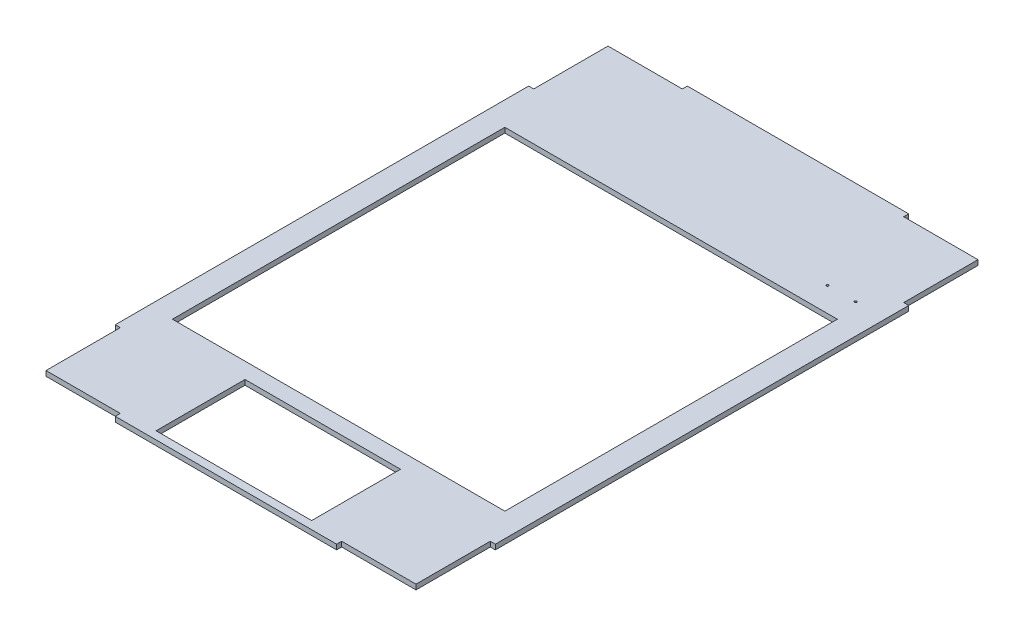
SolidWorks part; units mm, degrees
ref_plane "Front Plane" through (0, 0, 0) normal (0, 0, 1) x (1, 0, 0)
ref_plane "Top Plane" through (0, 0, 0) normal (0, 1, 0) x (1, 0, 0)
ref_plane "Right Plane" through (0, 0, 0) normal (1, 0, 0) x (0, 0, -1)
sketch "Sketch1" plane through (0, 0, 0) normal (0, 1, 0) x (1, 0, 0)
  line L1 (-209.5, -209.5) -> (209.5, -209.5)
  line L2 (-209.5, -209.5) -> (-209.5, 209.5)
  line L3 (-209.5, 209.5) -> (209.5, 209.5)
  line L4 (209.5, -209.5) -> (209.5, 209.5)
  line L5 (-209.5, -209.5) -> (209.5, 209.5) construction
  line L6 (-209.5, 209.5) -> (209.5, -209.5) construction
  line L7 (-239.5, -351.5) -> (239.5, -351.5)
  line L8 (-239.5, -351.5) -> (-239.5, 369.5)
  line L9 (-239.5, 369.5) -> (239.5, 369.5)
  line L10 (239.5, -351.5) -> (239.5, 369.5)
  line L11 (-98, -341.5) -> (98, -341.5)
  line L12 (-98, -341.5) -> (-98, -229.5)
  line L13 (-98, -229.5) -> (98, -229.5)
  line L14 (98, -341.5) -> (98, -229.5)
  line L15 (-98, -341.5) -> (98, -229.5) construction
  line L16 (-98, -229.5) -> (98, -341.5) construction
  point P0 (0, 0)
  point P6 (0, 0)
  point P11 (0, -351.5)
  point P12 (0, -285.5)
  dimension "D1" = 419
  dimension "D2" = 30
  dimension "D3" = 10
  dimension "D4" = 160
  dimension "D5" = 196
  dimension "D6" = 112
  dimension "D7" = 20
extrude "Boss-Extrude1" add sketch "Sketch1" along normal mid plane 6.35
sketch "Sketch2" plane through (0, 3.175, 0) normal (0, 1, 0) x (1, 0, 0)
  line L0 (-239.5, 369.5) -> (-239.5, 269.5)
  line L1 (-239.5, 369.5) -> (-239.5, -351.5) construction
  line L2 (-239.5, 269.5) -> (-233.15, 269.5)
  line L3 (-233.15, 269.5) -> (-233.15, 363.15)
  line L4 (-233.15, 363.15) -> (-139.5, 363.15)
  line L5 (-139.5, 363.15) -> (-139.5, 369.5)
  line L6 (239.5, 369.5) -> (-239.5, 369.5) construction
  line L7 (-139.5, 369.5) -> (-239.5, 369.5)
  line L8 (239.5, 369.5) -> (139.5, 369.5)
  line L9 (139.5, 369.5) -> (139.5, 363.15)
  line L10 (139.5, 363.15) -> (233.15, 363.15)
  line L11 (233.15, 363.15) -> (233.15, 269.5)
  line L12 (233.15, 269.5) -> (239.5, 269.5)
  line L13 (239.5, -351.5) -> (239.5, 369.5) construction
  line L14 (239.5, 269.5) -> (239.5, 369.5)
  line L15 (239.5, -351.5) -> (239.5, -251.5)
  line L16 (239.5, -251.5) -> (233.15, -251.5)
  line L17 (233.15, -251.5) -> (233.15, -345.15)
  line L18 (233.15, -345.15) -> (139.5, -345.15)
  line L19 (139.5, -345.15) -> (139.5, -351.5)
  line L20 (-239.5, -351.5) -> (239.5, -351.5) construction
  line L21 (139.5, -351.5) -> (239.5, -351.5)
  line L22 (-239.5, -351.5) -> (-139.5, -351.5)
  line L23 (-139.5, -351.5) -> (-139.5, -345.15)
  line L24 (-139.5, -345.15) -> (-233.15, -345.15)
  line L25 (-233.15, -345.15) -> (-233.15, -251.5)
  line L26 (-233.15, -251.5) -> (-239.5, -251.5)
  line L27 (-239.5, -251.5) -> (-239.5, -351.5)
  dimension "D1" = 100
  dimension "D2" = 6.35
extrude "Cut-Extrude1" cut sketch "Sketch2" against normal through all
sketch "Sketch3" plane through (0, 3.175, 0) normal (0, 1, 0) x (1, 0, 0)
  line L0 (201.88, 240.12) -> (166.32, 240.12) construction
  line L2 (209.5, 209.5) -> (-209.5, 209.5) construction
  line L3 (161.24, 232.5) -> (209.5, 232.5) construction
  line L4 (161.24, 232.5) -> (161.24, 268.06) construction
  line L5 (161.24, 268.06) -> (209.5, 268.06) construction
  line L6 (209.5, 232.5) -> (209.5, 268.06) construction
  line L7 (209.5, -209.5) -> (209.5, 209.5) construction
  circle A0 centre (166.32, 240.12) radius 1.375
  circle A1 centre (201.88, 240.12) radius 1.375
  dimension "D2" = 2.75
  dimension "D1" = 35.56
  dimension "D3" = 35.56
  dimension "D4" = 48.26
  dimension "D5" = 40.64
  dimension "D6" = 27.94
  dimension "D7" = 23
extrude "Cut-Extrude2" cut sketch "Sketch3" against normal through all
